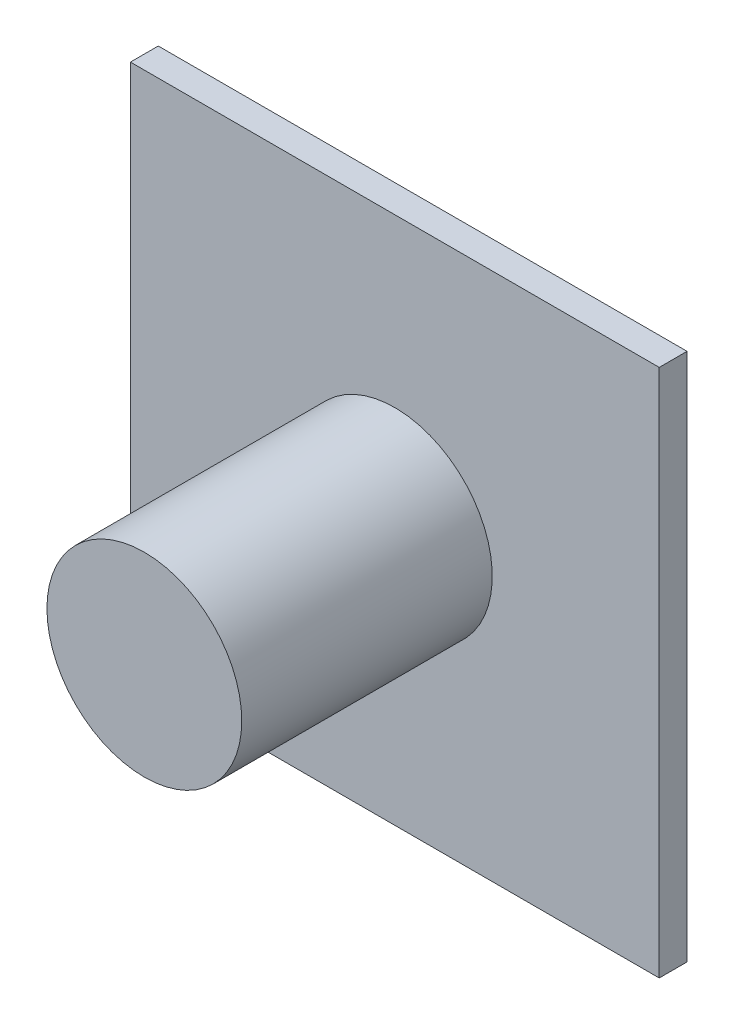
SolidWorks part; units mm, degrees
ref_plane "Front Plane" through (0, 0, 0) normal (0, 0, 1) x (1, 0, 0)
ref_plane "Top Plane" through (0, 0, 0) normal (0, 1, 0) x (1, 0, 0)
ref_plane "Right Plane" through (0, 0, 0) normal (1, 0, 0) x (0, 0, -1)
sketch "Sketch1" plane through (0, 0, 0) normal (0, 0, 1) x (1, 0, 0)
  line L1 (-19, -19) -> (19, -19)
  line L2 (-19, -19) -> (-19, 19)
  line L3 (-19, 19) -> (19, 19)
  line L4 (19, -19) -> (19, 19)
  line L5 (-19, -19) -> (19, 19) construction
  line L6 (-19, 19) -> (19, -19) construction
  point P0 (0, 0)
extrude "Boss-Extrude1" add sketch "Sketch1" along normal blind 2
sketch "Sketch2" plane through (0, 0, 0) normal (0, 0, 1) x (1, 0, 0)
  circle A0 centre (0, 0) radius 7
extrude "Boss-Extrude2" add sketch "Sketch2" along normal blind 20
